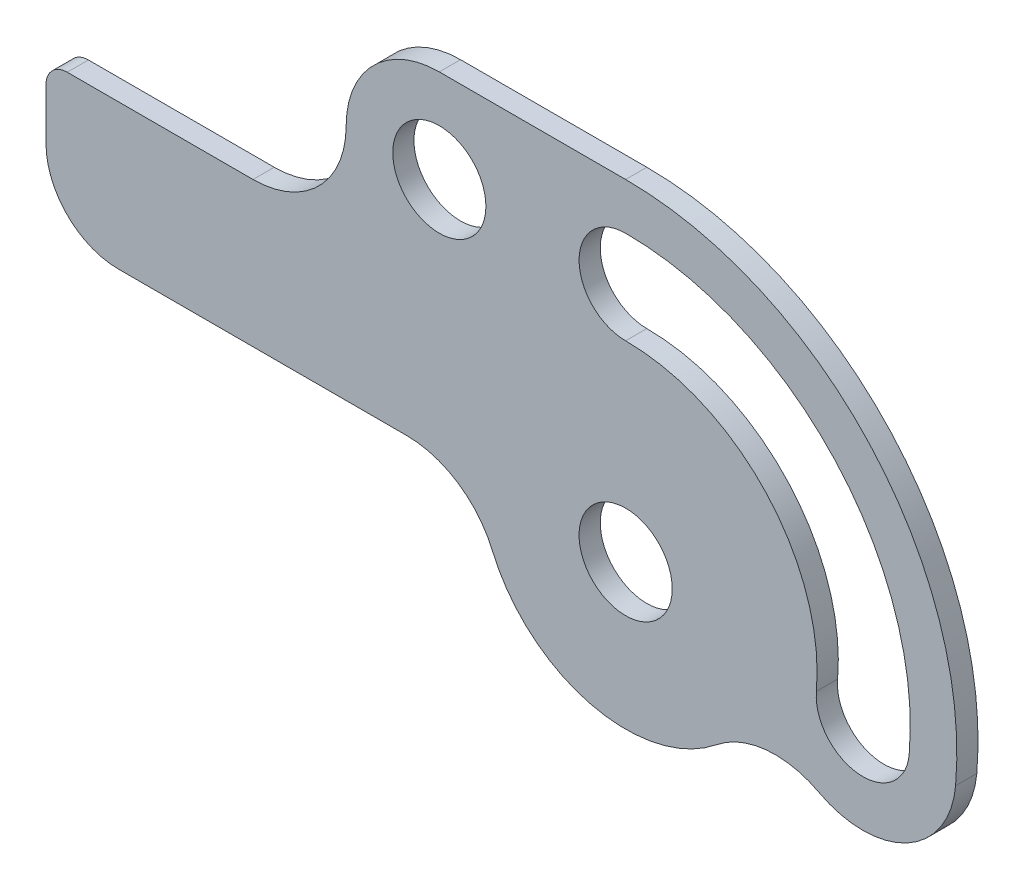
SolidWorks part; units mm, degrees
ref_plane "Front Plane" through (0, 0, 0) normal (0, 0, 1) x (1, 0, 0)
ref_plane "Top Plane" through (0, 0, 0) normal (0, 1, 0) x (1, 0, 0)
ref_plane "Right Plane" through (0, 0, 0) normal (1, 0, 0) x (0, 0, -1)
sketch "Sketch1" plane through (0, 0, 0) normal (0, 0, 1) x (1, 0, 0)
  line L0 (5.5562, 0) -> (16.6687, 0)
  line L1 (0, 5.5562) -> (22.225, 5.5562)
  line L2 (0, 5.5562) -> (0, -5.5562) construction
  line L3 (0, -5.5562) -> (22.225, -5.5562) construction
  line L4 (22.225, 5.5562) -> (22.225, -5.5562) construction
  line L5 (0, 5.5562) -> (22.225, 5.5562) construction
  line L6 (0, 5.5562) -> (0, -10.3188) construction
  line L7 (0, -10.3188) -> (22.225, -10.3188) construction
  line L8 (22.225, 5.5562) -> (22.225, -10.3188) construction
  line L9 (22.225, 0) -> (31.3184, -0.7956) construction
  line L10 (22.225, 9.1281) -> (22.225, 0) construction
  line L11 (5.5562, 0) -> (0, 0)
  line L12 (0, 0) -> (0, 5.5562)
  line L13 (15.0812, 12.7) -> (22.225, 12.7)
  circle A0 centre (0, 0) radius 5.5562 construction
  circle A1 centre (22.225, 0) radius 5.5562 construction
  arc A2 (0, 5.5562) -> (0, -5.5562) centre (0, 0) ccw
  arc A3 (22.225, -5.5562) -> (22.225, 5.5562) centre (22.225, 0) ccw
  circle A4 centre (0, 0) radius 1.7859
  circle A5 centre (22.225, 0) radius 1.7859
  arc A6 (0, -5.5562) -> (5.5562, 0) centre (0, 0) ccw
  arc A7 (16.6687, 0) -> (22.225, -5.5562) centre (22.225, 0) ccw
  circle A10 centre (0, 9.1281) radius 3.5719
  circle A12 centre (22.225, 9.1281) radius 1.7859
  circle A13 centre (31.3184, -0.7956) radius 3.5719
  circle A14 centre (31.3184, -0.7956) radius 1.7859
  circle A15 centre (0, 9.1281) radius 1.7859
  arc A16 (22.225, 9.1281) -> (31.3184, -0.7956) centre (22.225, 0) cw
  circle A17 centre (22.225, 9.1281) radius 3.5719
  circle A18 centre (7.1437, 9.1281) radius 3.5719
  circle A19 centre (15.0812, 9.1281) radius 3.5719
  arc A20 (22.225, 12.7) -> (34.8767, -1.1069) centre (22.225, 0) cw
  arc A21 (22.225, 10.9141) -> (33.0975, -0.9512) centre (22.225, 0) cw
  arc A22 (22.225, 7.3422) -> (29.5392, -0.6399) centre (22.225, 0) cw
  circle A23 centre (22.225, 0) radius 9.1281 construction
  circle A24 centre (27.9607, -7.101) radius 3.5719
  circle A25 centre (0, 0) radius 9.1281 construction
  circle A26 centre (-6.5741, 6.3327) radius 3.5719
  circle A27 centre (7.9375, 9.1281) radius 3.5719
  circle A28 centre (15.0812, 9.1281) radius 1.7859
  circle A29 centre (13.8247, -3.5719) radius 3.5719
  circle A30 centre (2.7781, 2.7781) radius 2.7781
  circle A31 centre (0.8137, 4.7426) radius 0.8137
  dimension "D1" = 22.225
  dimension "D2" = 11.1125
  dimension "D3" = 3.5719
  dimension "D5" = 95
  dimension "D6" = 7.1437
  dimension "D7" = 3.5719
  dimension "D4" = 15.875
extrude "Boss-Extrude1" add sketch "Sketch1" along normal blind 0.8128 contours L0 A7 A3 L1 A2 A6 A4 A5 | A19 L1 A17 | A22 A17 A3 A13 | A22 A12 A21 A17 | A17 A21 A13 A20 | A22 A13 A21 A14 | A24 A13 A3 | A19 A17 L13 | A19 A28 | A27 L1 A19 | A29 A7 L0 | A31 A30 A4 | A4 A30 | A30 A31 | A31 L12 A30 | A31 A30 L1 | A30 A31
